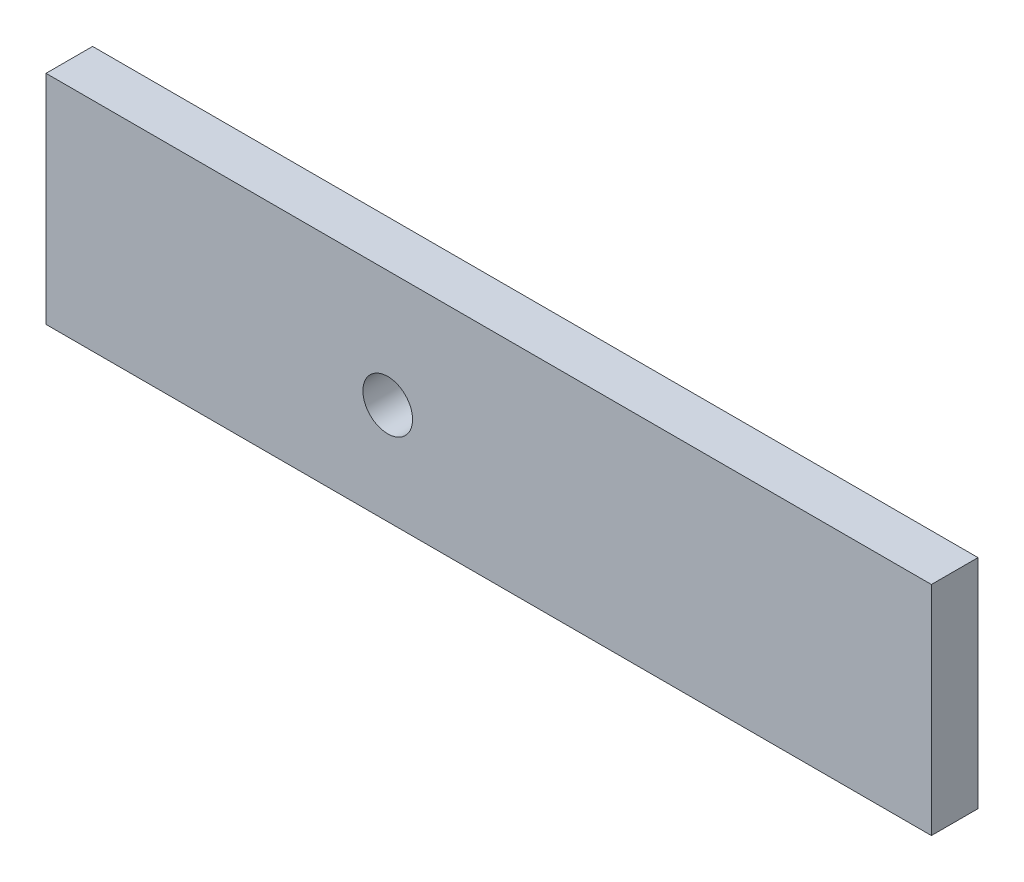
SolidWorks part; units mm, degrees
ref_plane "前视基准面" through (0, 0, 0) normal (0, 0, 1) x (1, 0, 0)
ref_plane "上视基准面" through (0, 0, 0) normal (0, 1, 0) x (1, 0, 0)
ref_plane "右视基准面" through (0, 0, 0) normal (1, 0, 0) x (0, 0, -1)
sketch "草图1" plane through (0, 0, 0) normal (0, 0, 1) x (1, 0, 0)
  line L0 (18.1, 0.8) -> (-10.4, 0.8)
  line L1 (-8.4, 0.8) -> (-1.9, 0.8) construction
  line L2 (18.1, 7.8) -> (18.1, 0.8)
  line L3 (-10.4, 0.8) -> (-10.4, 7.8)
  line L5 (-10.4, 7.8) -> (18.1, 7.8)
  line L6 (-10.4, 0) -> (-10.4, -1.5) construction
  line L7 (13.1, 0.8) -> (13.1, 5.8) construction
  circle A0 centre (0.6, 3.3) radius 1.75 construction
  circle A1 centre (0.6, 3.3) radius 1.75 construction
  circle A2 centre (0.6, 4.05) radius 1 construction
  dimension "D1" = 2
  dimension "D2" = 7
  dimension "D3" = 5
extrude "base" add sketch "草图1" along normal blind 1.5 contours L5 L2 L0 L3
sketch "草图4" plane through (0, 0, 0) normal (0, 0, -1) x (-1, 0, 0)
  circle A0 centre (-11.1, 3.3) radius 0.85 construction
  circle A1 centre (-11.1, 3.3) radius 0.85 construction
  circle A2 centre (-0.6, 3.3) radius 1.75 construction
  circle A3 centre (-0.6, 3.3) radius 1.75 construction
  circle A4 centre (-11.1, 3.3) radius 0.725
  dimension "D1" = 1.45
extrude "axis" add sketch "草图4" along normal offset from surface (1.9 mm away) 0.4
sketch "草图5" plane through (0, 0, 0) normal (0, 0, -1) x (-1, 0, 0)
  circle A0 centre (-0.6, 3.3) radius 1.75 construction
  circle A1 centre (-0.6, 3.3) radius 1.75 construction
  circle A2 centre (-0.6, 4.05) radius 1 construction
  point P5 (0, 0)
  dimension "D1" = 2
hole_wizard "M2 螺纹孔的螺纹孔钻头1" positions "3D草图1" profile "草图6" hole size "M2" standard "ISO" end condition up to next
sketch3d "3D草图1"
  point P0 (0.6, 4.05, 0)
sketch "草图6" plane through (0.6, 4.05, 0) normal (1, 0, 0) x (0, 1, 0)
  line L0 (0, 0) -> (0, 1.5)
  line L1 (0, 1.5) -> (0.8, 1.5)
  line L2 (0.8, 1.5) -> (0.8, 0)
  line L5 (0.8, 0) -> (0, 0)
  line L11 (0, -6.35) -> (0, 107.95) construction
  dimension "通孔孔直径" = 1.6
  dimension "通孔孔深度" = 1.5
sketch "草图7" plane through (0, 0, 1.5) normal (0, 0, 1) x (1, 0, 0)
  line L0 (18.1, 7.8) -> (18.1, 0.8) construction
  circle A0 centre (15.1, 4.05) radius 1
  dimension "D1" = 2
  dimension "D2" = 3
